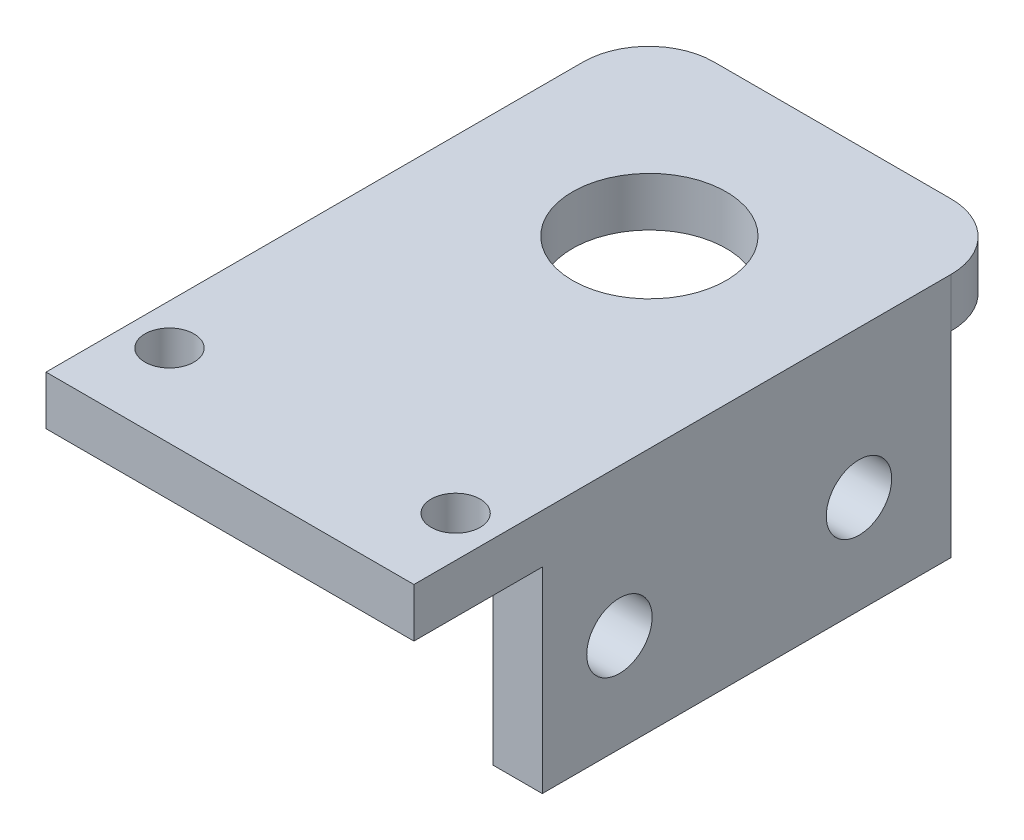
SolidWorks part; units mm, degrees
ref_plane "Front Plane" through (0, 0, 0) normal (0, 0, 1) x (1, 0, 0)
ref_plane "Top Plane" through (0, 0, 0) normal (0, 1, 0) x (1, 0, 0)
ref_plane "Right Plane" through (0, 0, 0) normal (1, 0, 0) x (0, 0, -1)
sketch "Sketch1" plane through (0, 0, 0) normal (0, 1, 0) x (1, 0, 0)
  line L4 (17.0455, 16.9573) -> (2.5455, 16.9573)
  line L5 (-1.4545, 12.9573) -> (-1.4545, -19.8927)
  line L6 (-1.4545, -19.8927) -> (2.7244, -19.8927)
  line L10 (16.8665, -19.8927) -> (21.0455, -19.8927)
  line L11 (21.0455, -19.8927) -> (21.0455, 12.9573)
  line L12 (-1.4545, -19.8927) -> (21.0455, -19.8927)
  circle A0 centre (1.0455, -14.8427) radius 1.5
  circle A1 centre (18.5455, -14.8427) radius 1.5
  arc A3 (2.5455, 16.9573) -> (-1.4545, 12.9573) centre (2.5455, 12.9573) ccw
  arc A4 (21.0455, 12.9573) -> (17.0455, 16.9573) centre (17.0455, 12.9573) ccw
  circle A5 centre (9.7955, 5.7573) radius 4.7
extrude "Boss-Extrude1" add sketch "Sketch1" along normal blind 3 contours L11 A4 L4 A3 L5 L6 L12 L10 A5 A0 A1
sketch "Sketch2" plane through (21.0455, 0, 0) normal (1, 0, 0) x (0, 0, -1)
  line L0 (-13.3427, 3) -> (-16.3427, 3) construction
  line L1 (-13.3427, 3) -> (-16.3427, 3)
  line L2 (-19.8927, 1.5) -> (-17.4694, 1.5)
  line L3 (12.9573, 3) -> (-12.0427, 3)
  line L4 (12.9573, 3) -> (12.9573, 15)
  line L5 (12.9573, 15) -> (-12.0427, 15)
  line L6 (-12.0427, 3) -> (-12.0427, 15)
  line L7 (-19.8927, 3) -> (-19.8927, 0) construction
  line L8 (-12.0427, 0) -> (-12.0427, -12)
  line L9 (12.9573, -12) -> (-12.0427, -12)
  line L10 (12.9573, 0) -> (12.9573, -12)
  line L11 (12.9573, 0) -> (-12.0427, 0)
  line M1 (-19.8927, 0) -> (12.9573, 0)
extrude "Boss-Extrude3" add sketch "Sketch2" against normal blind 3 contours L10 L8 L9 M1
sketch "Sketch4" plane through (18.0455, 0, 0) normal (-1, 0, 0) x (0, 0, 1)
  line L0 (0, 0) -> (0, -12)
  line L1 (-12.9573, -12) -> (12.0427, -12) construction
  line L2 (0, -6) -> (7.324, -6)
  circle A0 centre (7.324, -6) radius 2
  circle A1 centre (-7.324, -6) radius 2
extrude "Cut-Extrude2" cut sketch "Sketch4" against normal through all
ref_plane "Plane1" through (0, 0, 2.0427) normal (0, 0, 1) x (1, 0, 0)
sketch "Sketch5" plane through (0, 0, 2.0427) normal (0, 0, 1) x (1, 0, 0)
  line L0 (18.0455, -4.6412) -> (11.0112, 0)
  line L1 (18.0455, 0) -> (18.0455, -12) construction
  line L2 (-1.4545, 0) -> (21.0455, 0) construction
  line L3 (11.0112, 0) -> (18.0455, 0)
  line L4 (18.0455, 0) -> (18.0455, -4.6412)
extrude "Boss-Extrude4" add sketch "Sketch5" along normal mid plane 3
